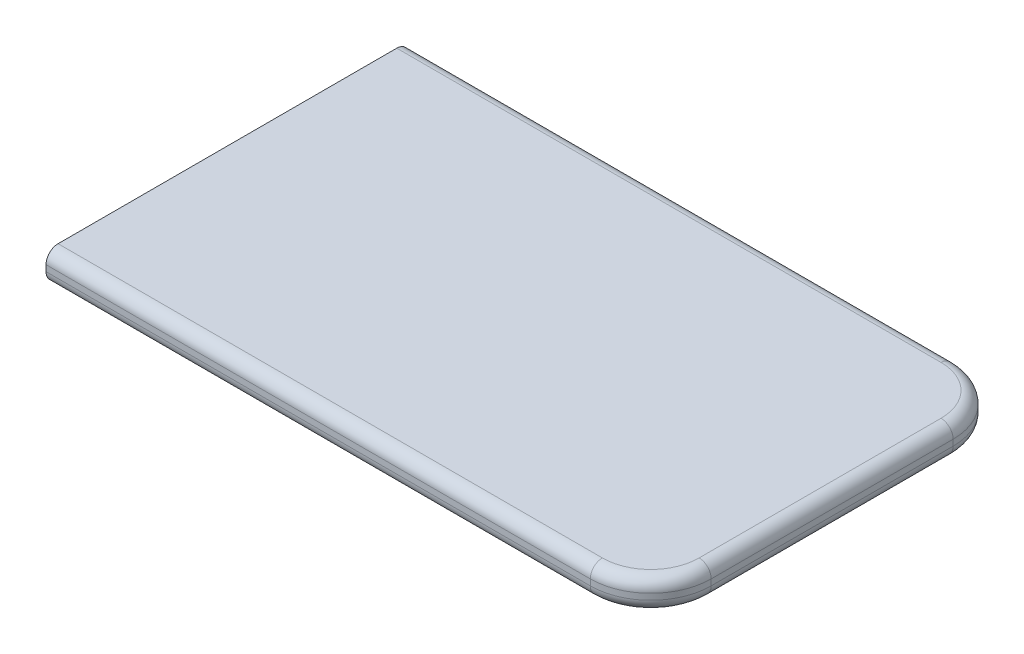
SolidWorks part; units mm, degrees
ref_plane "Front Plane" through (0, 0, 0) normal (0, 0, 1) x (1, 0, 0)
ref_plane "Top Plane" through (0, 0, 0) normal (0, 1, 0) x (1, 0, 0)
ref_plane "Right Plane" through (0, 0, 0) normal (1, 0, 0) x (0, 0, -1)
sketch "Sketch1" plane through (0, 0, 0) normal (0, 1, 0) x (1, 0, 0)
  line L0 (0, 0) -> (0, 600)
  line L1 (0, 0) -> (-1000, 0)
  line L3 (0, 600) -> (-1000, 600)
  line L4 (-1000, 0) -> (-1000, 600)
  dimension "D1" = 1000
  dimension "D2" = 600
extrude "Boss-Extrude1" add sketch "Sketch1" along normal blind 50 contours L1 L4 L3 L0
fillet "Fillet1" radius 100 2 edges at (0, 25, -600) (0, 25, 0)
fillet "Fillet2" radius 20 10 edges at (-550, 0, -600) (-29.2893, 0, -570.7107) (0, 0, -300) (-29.2893, 0, -29.2893) (-550, 50, -600) (-29.2893, 50, -570.7107) (0, 50, -300) (-29.2893, 50, -29.2893) (-550, 0, 0) (-550, 50, 0)
